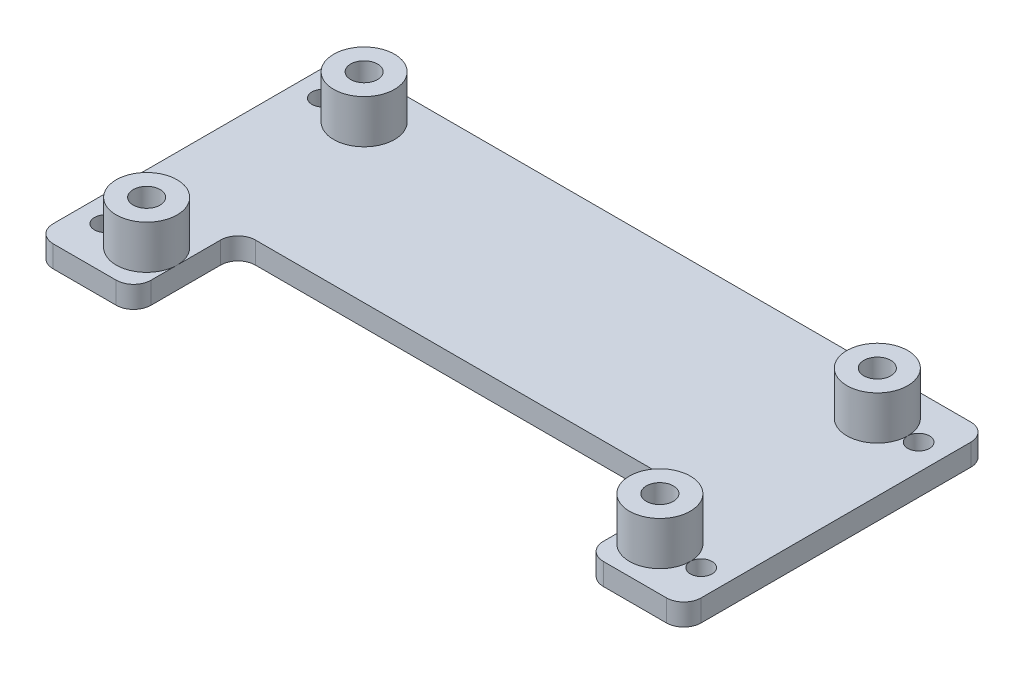
SolidWorks part; units mm, degrees
ref_plane "Front Plane" through (0, 0, 0) normal (0, 0, 1) x (1, 0, 0)
ref_plane "Top Plane" through (0, 0, 0) normal (0, 1, 0) x (1, 0, 0)
ref_plane "Right Plane" through (0, 0, 0) normal (1, 0, 0) x (0, 0, -1)
sketch "Sketch1" plane through (0, 0, 0) normal (0, 1, 0) x (1, 0, 0)
  line L1 (0, 0) -> (94.615, 0)
  line L2 (0, 0) -> (0, 44.45)
  line L3 (0, 44.45) -> (94.615, 44.45)
  line L4 (94.615, 0) -> (94.615, 44.45)
  dimension "D1" = 44.45
  dimension "D2" = 94.615
extrude "Boss-Extrude1" add sketch "Sketch1" along normal blind 3.175 contours L2 L1 L4 L3
sketch "Sketch2" plane through (0, 3.175, 0) normal (0, 1, 0) x (1, 0, 0)
  line L0 (0, 44.45) -> (94.615, 44.45) construction
  line L1 (0, 0) -> (0, 44.45) construction
  circle A0 centre (9.8425, 38.1) radius 1.9685
  circle A2 centre (9.8425, 6.35) radius 1.9685
  circle A3 centre (84.7725, 38.1) radius 1.9685
  circle A4 centre (84.7725, 6.35) radius 1.9685
  circle A5 centre (9.8425, 6.35) radius 4.445
  circle A6 centre (9.8425, 38.1) radius 4.445
  circle A7 centre (84.7725, 38.1) radius 4.445
  circle A8 centre (84.7725, 6.35) radius 4.445
  dimension "D1" = 3.937
  dimension "D6" = 8.89
  dimension "D2" = 31.75
  dimension "D3" = 74.93
  dimension "D4" = 6.35
  dimension "D5" = 9.8425
extrude "Boss-Extrude2" add sketch "Sketch2" along normal blind 6.35
sketch "Sketch4" plane through (0, 3.175, 0) normal (0, 1, 0) x (1, 0, 0)
  circle A0 centre (3.81, 38.1) radius 1.5875
  circle A1 centre (3.81, 6.35) radius 1.5875
  circle A2 centre (9.8425, 6.35) radius 1.9685 construction
  circle A3 centre (9.8425, 38.1) radius 1.9685 construction
  circle A4 centre (9.8425, 38.1) radius 1.9685 construction
  circle A5 centre (90.805, 38.1) radius 1.5875
  circle A6 centre (90.805, 6.35) radius 1.5875
  dimension "D1" = 3.175
  dimension "D2" = 3.175
  dimension "D3" = 6.0325
  dimension "D4" = 6.0325
  dimension "D5" = 0
  dimension "D6" = 31.75
  dimension "D7" = 2
extrude "Cut-Extrude1" cut sketch "Sketch4" against normal blind 6.35
fillet "Fillet1" radius 2.54 4 edges at (94.615, 1.5875, -44.45) (94.615, 1.5875, 0) (0, 1.5875, -44.45) (0, 1.5875, 0)
sketch "Sketch6" plane through (0, 3.175, 0) normal (0, 1, 0) x (1, 0, 0)
  line L0 (2.54, 0) -> (92.075, 0) construction
  line L1 (14.2875, 0) -> (80.3275, 0)
  line L2 (14.2875, 0) -> (14.2875, 15.24)
  line L3 (14.2875, 15.24) -> (80.3275, 15.24)
  line L4 (80.3275, 0) -> (80.3275, 15.24)
  circle A0 centre (9.8425, 6.35) radius 4.445 construction
  circle A1 centre (84.7725, 6.35) radius 4.445 construction
  dimension "D1" = 4.445
  dimension "D2" = 4.445
  dimension "D3" = 15.24
extrude "Cut-Extrude2" cut sketch "Sketch6" against normal blind 5.08
fillet "Fillet2" radius 2.54 4 edges at (14.2875, 1.5875, 0) (14.2875, 1.5875, -15.24) (80.3275, 1.5875, -15.24) (80.3275, 1.5875, 0)
